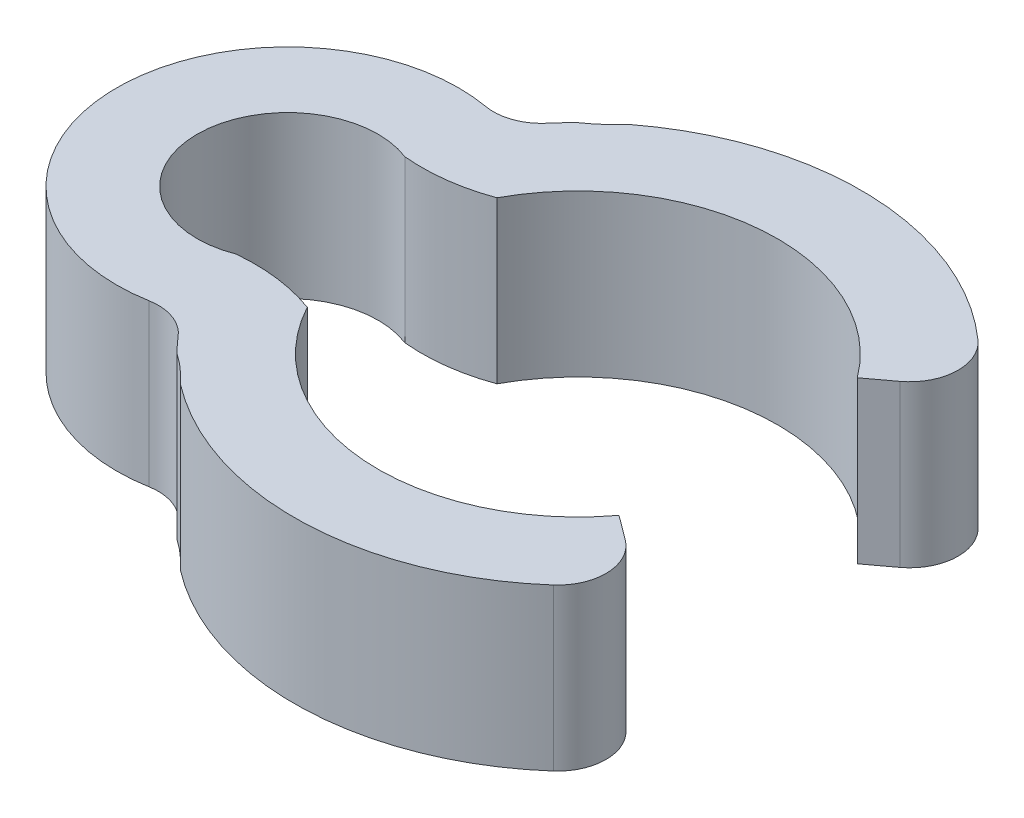
SolidWorks part; units mm, degrees
ref_plane "Front Plane" through (0, 0, 0) normal (0, 0, 1) x (1, 0, 0)
ref_plane "Top Plane" through (0, 0, 0) normal (0, 1, 0) x (1, 0, 0)
ref_plane "Right Plane" through (0, 0, 0) normal (1, 0, 0) x (0, 0, -1)
sketch "Sketch1" plane through (0, 0, 0) normal (0, 1, 0) x (1, 0, 0)
  line L0 (-89.7023, 5.6709) -> (-53.6803, 5.6709) construction
  line L1 (-66.0739, 13.0645) -> (-34.5365, 13.0645)
  line L2 (-66.0739, 18.0645) -> (-34.5365, 18.0645)
  line L3 (-66.0739, 18.0645) -> (-66.0739, 5.6709)
  line L4 (-66.0739, 5.6709) -> (-34.5365, 5.6709)
  line L5 (-34.5365, 18.0645) -> (-34.5365, 5.6709)
  line L6 (-66.0739, 5.6709) -> (-56.1272, 13.0645)
  line L7 (-56.1272, 13.0645) -> (-51.956, 16.1651)
  line L8 (-56.1272, -1.7227) -> (-51.956, -4.8233)
  circle A1 centre (-66.0739, 5.6709) radius 12.3936
  circle A2 centre (-84.0849, 5.6709) radius 5.6174
  arc A3 (-84.0849, 11.2883) -> (-76.9812, 11.5558) centre (-80.9464, 22.3989) ccw
  arc A4 (-84.0849, 0.0535) -> (-76.9812, -0.214) centre (-80.9464, -11.0571) cw
  circle A5 centre (-66.0739, 5.6709) radius 17.591
  circle A6 centre (-84.0849, 5.6709) radius 10.6064
  arc A7 (-84.0849, 16.2773) -> (-76.7956, 19.6168) centre (-84.2931, 26.3568) ccw
  arc A8 (-84.0849, -4.9355) -> (-76.7956, -8.275) centre (-84.2931, -15.015) cw
  point P21 (-53.6803, 5.6709)
  dimension "D1" = 5
extrude "Boss-Extrude3" add sketch "Sketch1" along normal blind 10 contours L7 A5 L2 A1 | A7 A5 A6 A1 L2 | A1 A6 A5 A2 A3 | A5 A6 A2 | A5 A6 A1 A4 A2 | A5 A8 L8 A1 A6
fillet "Fillet3" radius 3 4 edges at (-80.5468, 5, 4.3279) (-80.5468, 5, -15.6698) (-51.956, 5, 4.8233) (-51.956, 5, -16.1651)
